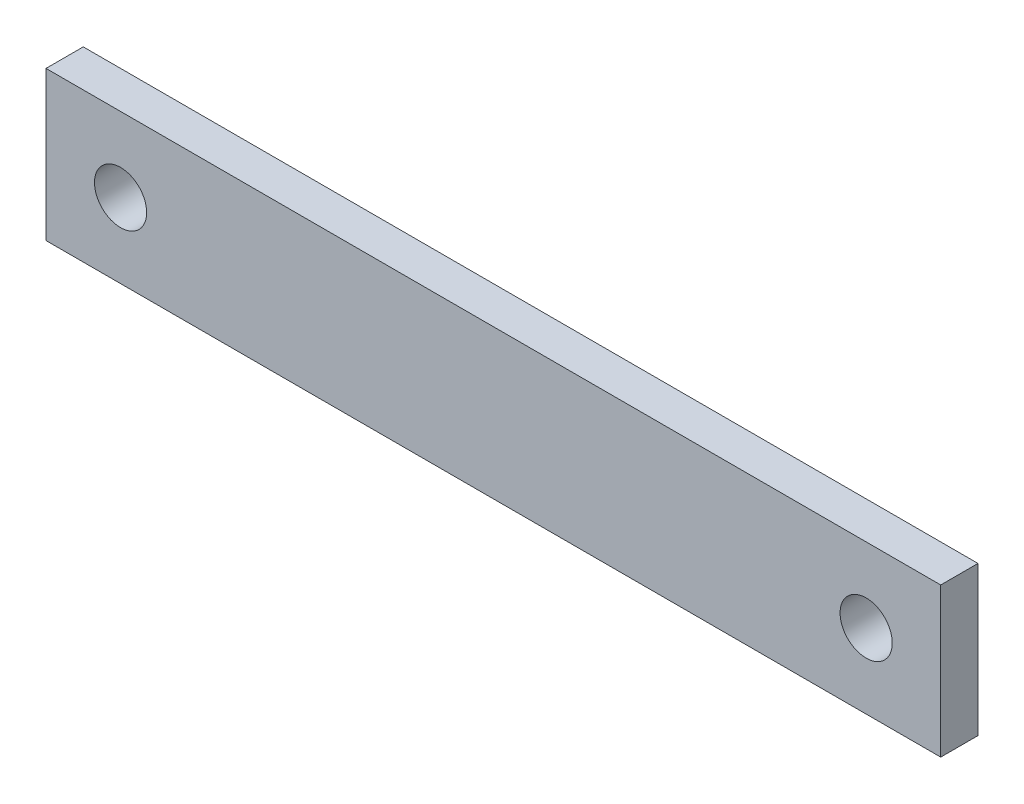
SolidWorks part; units mm, degrees
material "ASTM A36 Steel"
ref_plane "Front Plane" through (0, 0, 0) normal (0, 0, 1) x (1, 0, 0)
ref_plane "Top Plane" through (0, 0, 0) normal (0, 1, 0) x (1, 0, 0)
ref_plane "Right Plane" through (0, 0, 0) normal (1, 0, 0) x (0, 0, -1)
sketch "Sketch1" plane through (0, 0, 0) normal (0, 0, 1) x (1, 0, 0)
  line L1 (-120, -20) -> (120, -20)
  line L2 (-120, -20) -> (-120, 20)
  line L3 (-120, 20) -> (120, 20)
  line L4 (120, -20) -> (120, 20)
  line L5 (-120, -20) -> (120, 20) construction
  line L6 (-120, 20) -> (120, -20) construction
  circle A0 centre (-100, 0) radius 7
  circle A1 centre (100, 0) radius 7
  point P0 (0, 0)
  dimension "D3" = 14
  dimension "D4" = 14
  dimension "D5" = 20
  dimension "D6" = 20
  dimension "D7" = 20
  dimension "D8" = 20
  dimension "D1" = 240
  dimension "D2" = 40
extrude "Boss-Extrude1" add sketch "Sketch1" along normal blind 10
